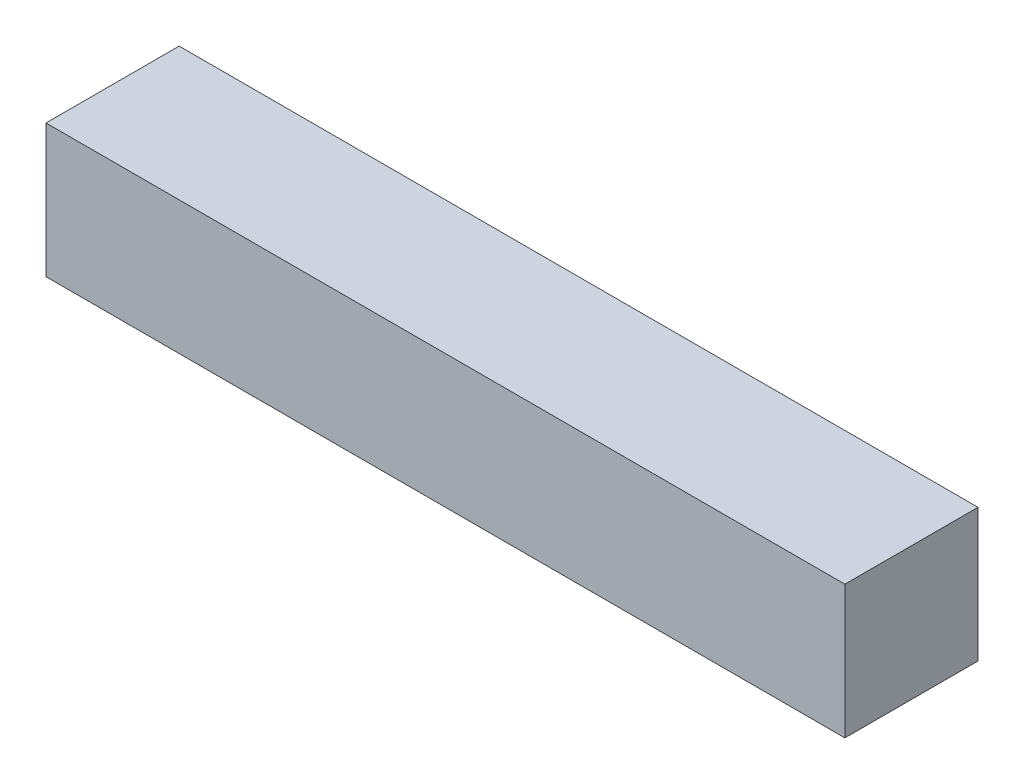
SolidWorks part; units mm, degrees
material "Plain Carbon Steel"
ref_plane "Front Plane" through (0, 0, 0) normal (0, 0, 1) x (1, 0, 0)
ref_plane "Top Plane" through (0, 0, 0) normal (0, 1, 0) x (1, 0, 0)
ref_plane "Right Plane" through (0, 0, 0) normal (1, 0, 0) x (0, 0, -1)
sketch "Sketch1" plane through (0, 0, 0) normal (0, 0, 1) x (1, 0, 0)
  line L1 (-19.05, -3.175) -> (19.05, -3.175)
  line L2 (-19.05, -3.175) -> (-19.05, 3.175)
  line L3 (-19.05, 3.175) -> (19.05, 3.175)
  line L4 (19.05, -3.175) -> (19.05, 3.175)
  line L5 (-19.05, -3.175) -> (19.05, 3.175) construction
  line L6 (-19.05, 3.175) -> (19.05, -3.175) construction
  point P0 (0, 0)
  dimension "D1" = 38.1
  dimension "D2" = 6.35
extrude "Extrude1" add sketch "Sketch1" along normal blind 6.35
